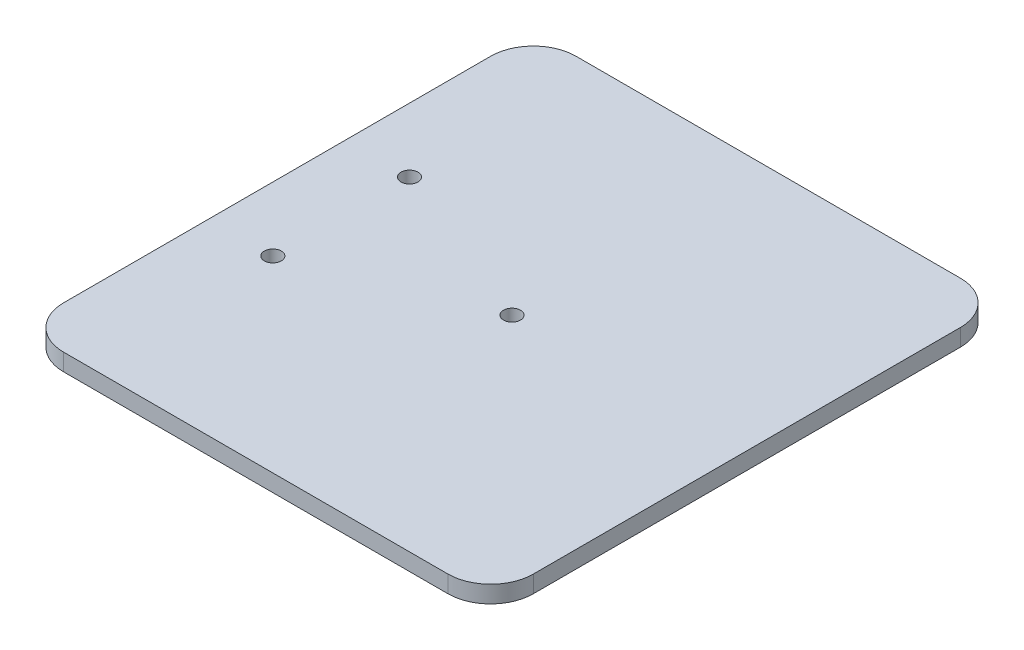
SolidWorks part; units mm, degrees
ref_plane "Front Plane" through (0, 0, 0) normal (0, 0, 1) x (1, 0, 0)
ref_plane "Top Plane" through (0, 0, 0) normal (0, 1, 0) x (1, 0, 0)
ref_plane "Right Plane" through (0, 0, 0) normal (1, 0, 0) x (0, 0, -1)
sketch "Sketch1" plane through (0, 0, 0) normal (0, 1, 0) x (1, 0, 0)
  line L1 (-36.8009, 29.8578) -> (8.1991, 29.8578)
  line L2 (-41.8009, 24.8578) -> (-41.8009, -25.1422)
  line L3 (-36.8009, -30.1422) -> (8.1991, -30.1422)
  line L4 (13.1991, 24.8578) -> (13.1991, -25.1422)
  arc A0 (8.1991, -30.1422) -> (13.1991, -25.1422) centre (8.1991, -25.1422) ccw
  arc A1 (-41.8009, -25.1422) -> (-36.8009, -30.1422) centre (-36.8009, -25.1422) ccw
  arc A2 (8.1991, 29.8578) -> (13.1991, 24.8578) centre (8.1991, 24.8578) cw
  arc A3 (-41.8009, 24.8578) -> (-36.8009, 29.8578) centre (-36.8009, 24.8578) cw
  circle A4 centre (-34.3009, 7.8578) radius 1
  circle A5 centre (-34.3009, -8.1422) radius 1
  circle A6 centre (-14.3009, -0.1422) radius 1
  point P8 (-41.8009, -30.1422)
  point P11 (13.1991, 29.8578)
  point P14 (-41.8009, 29.8578)
  dimension "D3" = 5
  dimension "D4" = 7.5
  dimension "D6" = 22
  dimension "D7" = 30
  dimension "D1" = 60
  dimension "D2" = 55
  dimension "D5" = 22
  dimension "D8" = 27.5
extrude "Boss-Extrude1" add sketch "Sketch1" along normal blind 2
